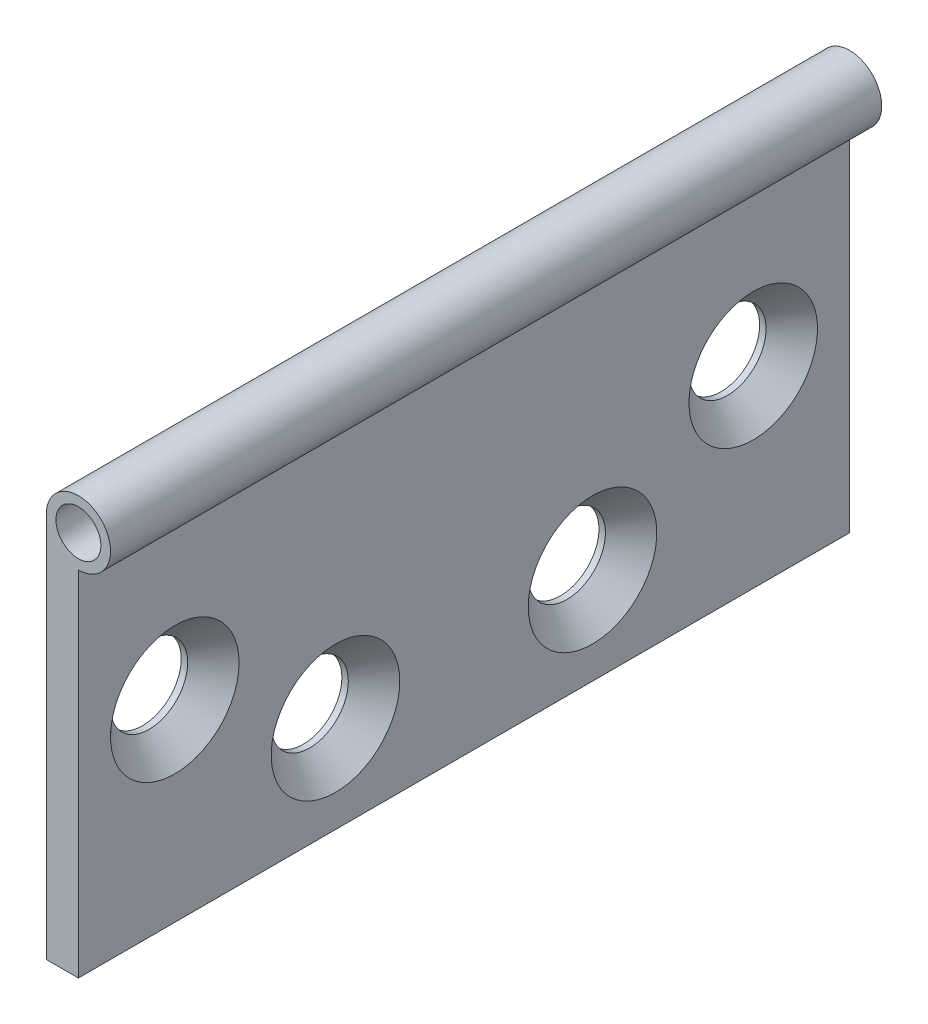
SolidWorks part; units mm, degrees
ref_plane "Спереди" through (0, 0, 0) normal (0, 0, 1) x (1, 0, 0)
ref_plane "Сверху" through (0, 0, 0) normal (0, 1, 0) x (1, 0, 0)
ref_plane "Справа" through (0, 0, 0) normal (1, 0, 0) x (0, 0, -1)
sketch "Эскиз1" plane through (0, 0, 0) normal (0, 0, 1) x (1, 0, 0)
  line L0 (0, 0) -> (0, 60)
  dimension "D1" = 60
extrude "Вытянуть-Тонкостенный2" add sketch "Эскиз1" along normal mid plane 120 thin contours L0
sketch "Эскиз2" plane through (0, 0, 60) normal (0, 0, 1) x (1, 0, 0)
  circle A0 centre (5, 60) radius 5
sweep "По траектории1" add profiles "Эскиз2" path edge at (0, 60, 0)
sketch "Эскиз3" plane through (0, 0, 60) normal (0, 0, 1) x (1, 0, 0)
  circle A0 centre (5, 60) radius 3.5
  dimension "D1" = 7
extrude "Вырез-Вытянуть1" cut sketch "Эскиз3" against normal through all
hole_wizard "Зенковка для  винта с плоской головкой M101" positions "Эскиз7" profile "Эскиз8" countersink size "M10" standard "Ansi Metric" end condition through all
sketch "Эскиз7" plane through (5, 0, 0) normal (1, 0, 0) x (0, 0, -1)
  line L0 (-60, 0) -> (-60, 55) construction
  line L1 (-60, 0) -> (60, 0) construction
  point P0 (-45, 30)
  point P2 (-20, 15)
  point P9 (0, 0)
  dimension "D1" = 15
  dimension "D2" = 30
  dimension "D3" = 40
  dimension "D4" = 15
sketch "Эскиз8" plane through (5, 30, 45) normal (0, 1, 0) x (0, 0, -1)
  line L0 (0, 0) -> (0, 5)
  line L1 (0, 5) -> (6, 5)
  line L2 (6, 5) -> (6, 4)
  line L3 (6, 4) -> (10, 0)
  line L5 (10, 0) -> (0, 0)
  line L6 (-6, 4) -> (-10, 0) construction
  line L11 (0, -6.35) -> (0, 107.95) construction
  dimension "Диаметр сквозного отверстия" = 12
  dimension "Глубина сквозного отверстия" = 5
  dimension "Диаметр передней зенковки" = 20
  dimension "Угол передней зенковки" = 90
mirror "Зеркальное отражение1" about plane through (0, 0, 0) normal (0, 0, 1) of "Зенковка для  винта с плоской головкой M101"
equation "\"depth\"= 5"
equation "\"width\"= 60"
equation "\"length\"= 120"
equation "\"D1@Вытянуть-Тонкостенный2\"= \"length\""
equation "\"D1@Эскиз1\"= \"width\""
equation "\"D5@Вытянуть-Тонкостенный2\"= \"depth\""
equation "\"D1@Эскиз3\"= \"depth\" / 5 * 7"
equation "\"D1@Эскиз7\"= \"length\" / 8"
equation "\"D2@Эскиз7\"= \"width\" / 2"
equation "\"D3@Эскиз7\"= \"length\" / 3"
equation "\"D4@Эскиз7\"= \"width\" / 4"
equation "\"D4@Эскиз4\"= \"length\" / 3"
equation "\"D3@Эскиз4\"= \"width\" / 2"
equation "\"D2@Эскиз4\"= \"width\" / 4"
equation "\"D1@Эскиз4\"= \"width\" / 4"
